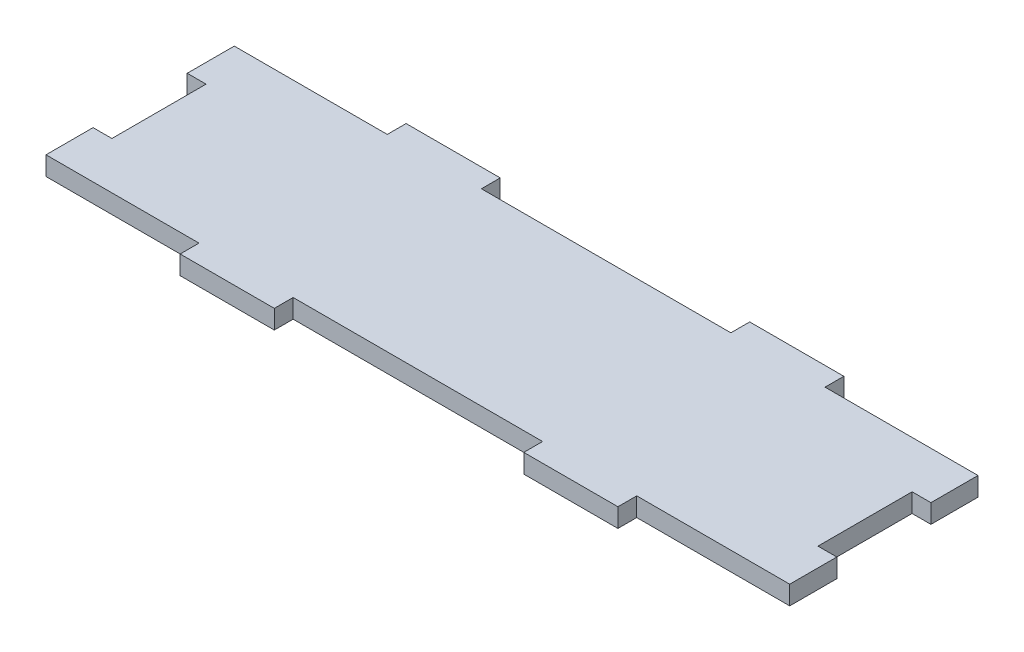
SolidWorks part; units mm, degrees
ref_plane "Alzado" through (0, 0, 0) normal (0, 0, 1) x (1, 0, 0)
ref_plane "Planta" through (0, 0, 0) normal (0, 1, 0) x (1, 0, 0)
ref_plane "Vista lateral" through (0, 0, 0) normal (1, 0, 0) x (0, 0, -1)
sketch "Croquis1" plane through (0, 0, 0) normal (0, 1, 0) x (1, 0, 0)
  line L0 (75, 0) -> (75, 40) construction
  line L1 (0, 0) -> (28.5, 0)
  line L3 (0, 40) -> (28.5, 40)
  line L6 (28.5, 40) -> (28.5, 44)
  line L7 (28.5, 44) -> (48.5, 44)
  line L8 (48.5, 40) -> (48.5, 44)
  line L10 (28.5, 0) -> (28.5, -4)
  line L11 (28.5, -4) -> (48.5, -4)
  line L12 (48.5, 0) -> (48.5, -4)
  line L17 (75, 20) -> (0, 20) construction
  line L18 (-4, 20) -> (0, 20) construction
  line L19 (37.5, 20) -> (37.5, 42.0443) construction
  line L20 (37.5, 20) -> (37.5, -4) construction
  line L21 (121.5, 40) -> (121.5, 44)
  line L22 (101.5, 40) -> (101.5, 44)
  line L23 (121.5, 44) -> (101.5, 44)
  line L24 (101.5, 0) -> (101.5, -4)
  line L25 (121.5, -4) -> (101.5, -4)
  line L26 (121.5, 0) -> (121.5, -4)
  line L31 (48.5, 0) -> (101.5, 0)
  line L32 (48.5, 40) -> (101.5, 40)
  line L33 (0, 34.8259) -> (75, 34.8259) construction
  line L34 (75, 34.8259) -> (150, 34.8259) construction
  line L35 (121.5, 40) -> (150, 40)
  line L37 (121.5, 0) -> (150, 0)
  line L45 (0, 0) -> (-4, 0)
  line L46 (-4, 0) -> (-4, 10)
  line L47 (-4, 10) -> (0, 10)
  line L48 (0, 10) -> (0, 30)
  line L49 (0, 30) -> (-4, 30)
  line L50 (-4, 30) -> (-4, 40)
  line L51 (-4, 40) -> (0, 40)
  line L52 (150, 40) -> (150, 0) construction
  line L53 (0, 30) -> (0, 40) construction
  line L54 (0, 30) -> (75, 30) construction
  line L55 (150, 0) -> (154, 0)
  line L56 (154, 0) -> (154, 10)
  line L57 (154, 10) -> (150, 10)
  line L58 (150, 10) -> (150, 30)
  line L59 (150, 30) -> (154, 30)
  line L60 (154, 30) -> (154, 40)
  line L61 (154, 40) -> (150, 40)
  point P13 (0, 20)
  point P39 (37.5, 31.0222)
  point P40 (37.5, 34.8259)
  dimension "D1" = 150
  dimension "D2" = 40
  dimension "D3" = 4
  dimension "D4" = 20
  dimension "D5" = 26.5
extrude "Saliente-Extruir1" add sketch "Croquis1" along normal blind 4
